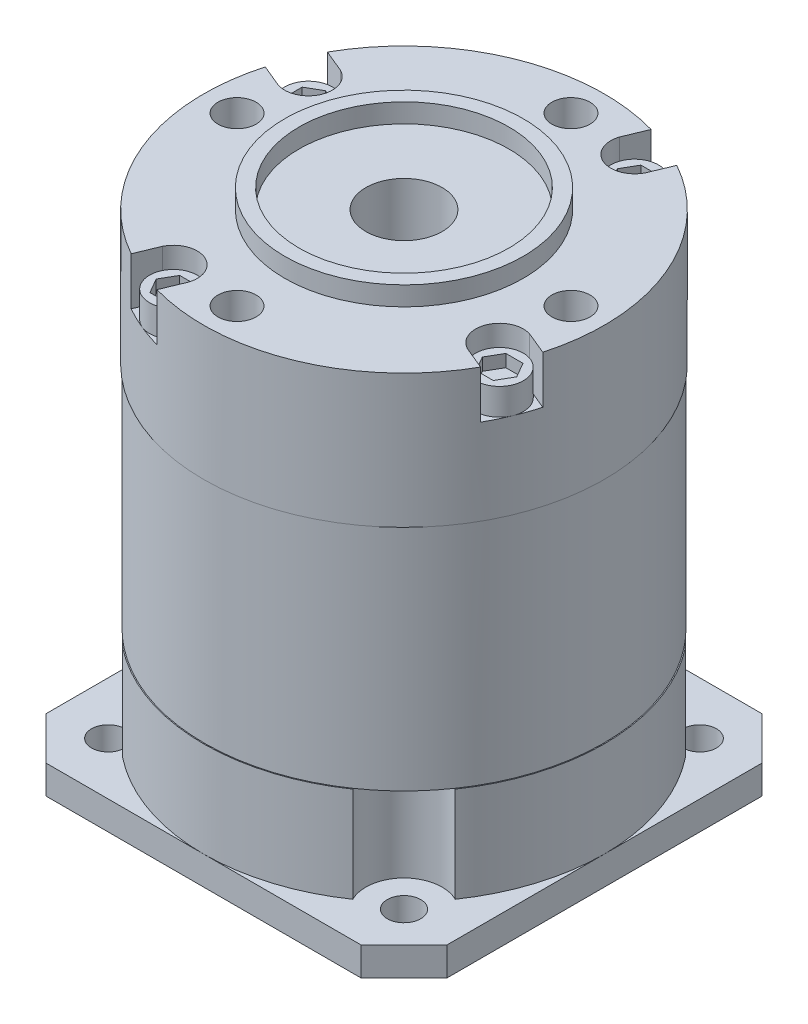
SolidWorks part; units mm, degrees
ref_plane "前视基准面" through (0, 0, 0) normal (0, 0, 1) x (1, 0, 0)
ref_plane "上视基准面" through (0, 0, 0) normal (0, 1, 0) x (1, 0, 0)
ref_plane "右视基准面" through (0, 0, 0) normal (1, 0, 0) x (0, 0, -1)
other "Configuration Table"
sketch "草图1" plane through (0, 0, 0) normal (0, 1, 0) x (1, 0, 0)
  line L1 (-21, 21) -> (21, 21)
  line L2 (-21, 21) -> (-21, -21)
  line L3 (-21, -21) -> (21, -21)
  line L4 (21, 21) -> (21, -21)
  line L5 (-21, 21) -> (21, -21) construction
  line L6 (-21, -21) -> (21, 21) construction
  point P0 (0, 0)
  dimension "D1" = 42
  dimension "D2" = 42
extrude "凸台-拉伸1" add sketch "草图1" along normal blind 3
sketch "草图2" plane through (0, 0, 0) normal (0, 1, 0) x (1, 0, 0)
  line L0 (-1000, 0) -> (49000, 0) construction
  line L1 (0, -1000) -> (0, 49000) construction
  line L2 (-21, 21) -> (-21, 16.5)
  line L3 (-21, 21) -> (-21, -21) construction
  line L4 (-21, 16.5) -> (-16.5, 21)
  line L5 (21, 21) -> (-21, 21) construction
  line L6 (-16.5, 21) -> (-21, 21)
  line L7 (16.5, 21) -> (21, 21)
  line L8 (21, 16.5) -> (16.5, 21)
  line L9 (21, 21) -> (21, 16.5)
  line L10 (21, -21) -> (21, -16.5)
  line L11 (21, -16.5) -> (16.5, -21)
  line L12 (16.5, -21) -> (21, -21)
  line L13 (-16.5, -21) -> (-21, -21)
  line L14 (-21, -16.5) -> (-16.5, -21)
  line L15 (-21, -21) -> (-21, -16.5)
  dimension "D1" = 4.5
  dimension "D2" = 4.5
extrude "切除-拉伸1" cut sketch "草图2" against normal up to surface (3 mm away) from surface at 3 up to face at (0, 0, 0) starting at face at (0, 3, 0)
sketch "草图3" plane through (0, 0, 0) normal (0, 1, 0) x (1, 0, 0)
  circle A0 centre (0, 0) radius 21
  dimension "D1" = 42
extrude "凸台-拉伸2" add sketch "草图3" along normal blind 51
sketch "草图5" plane through (0, 0, 0) normal (0, 1, 0) x (1, 0, 0)
  line L1 (-15.5, 15.5) -> (15.5, 15.5) construction
  line L2 (-15.5, 15.5) -> (-15.5, -15.5) construction
  line L3 (-15.5, -15.5) -> (15.5, -15.5) construction
  line L4 (15.5, 15.5) -> (15.5, -15.5) construction
  line L5 (-15.5, 15.5) -> (15.5, -15.5) construction
  line L6 (-15.5, -15.5) -> (15.5, 15.5) construction
  circle A0 centre (-15.5, 15.5) radius 1.75
  circle A1 centre (15.5, 15.5) radius 1.75
  circle A2 centre (-15.5, -15.5) radius 1.75
  circle A3 centre (15.5, -15.5) radius 1.75
  point P0 (0, 0)
  dimension "D3" = 3.5
  dimension "D4" = 3.5
  dimension "D5" = 3.5
  dimension "D6" = 3.5
  dimension "D1" = 31
  dimension "D2" = 31
extrude "切除-拉伸3" cut sketch "草图5" along normal up to surface (3 mm away) from surface at 0 up to face at (15.7123, 3, 15.7123) starting at face at (0, 0, 0)
sketch "草图7" plane through (0, 0, 0) normal (0, 1, 0) x (1, 0, 0)
  circle A0 centre (-15.5, 15.5) radius 2.75
  circle A1 centre (15.5, 15.5) radius 2.75
  circle A2 centre (-15.5, -15.5) radius 2.75
  circle A3 centre (15.5, -15.5) radius 4
  dimension "D1" = 5.5
  dimension "D2" = 5.5
  dimension "D3" = 5.5
  dimension "D4" = 8
extrude "切除-拉伸4" cut sketch "草图7" along normal blind 10 from surface at 3 starting at face at (15.2941, 3, -15.2941)
sketch "草图8" plane through (0, 0, 0) normal (0, 1, 0) x (1, 0, 0)
  circle A0 centre (0, 0) radius 20.9
  circle A1 centre (0, 0) radius 21
  dimension "D1" = 41.8
  dimension "D2" = 42
extrude "切除-拉伸5" cut sketch "草图8" along normal blind 24 from surface at 13 starting at face at (13.7604, 13, 13.7604)
sketch "草图9" plane through (0, 0, 0) normal (0, 1, 0) x (1, 0, 0)
  circle A0 centre (0, 0) radius 12.5
  dimension "D1" = 25
extrude "凸台-拉伸3" add sketch "草图9" along normal blind 2 from surface at 51 starting at face at (0, 51, 21)
sketch "草图11" plane through (0, 0, 0) normal (0, 1, 0) x (1, 0, 0)
  line L0 (-1000, 0) -> (49000, 0) construction
  line L1 (0, -1000) -> (0, 49000) construction
  circle A0 centre (0, 0) radius 17.5 construction
  circle A1 centre (-17.5, 0) radius 2
  circle A2 centre (0, -17.5) radius 2
  circle A3 centre (17.5, 0) radius 2
  circle A4 centre (0, 17.5) radius 2
  point P7 (0, 17.5)
  point P8 (-17.5, 0)
  point P9 (17.5, 0)
  point P10 (0, -17.5)
  point P11 (22.5067, -42.5527)
  dimension "D1" = 35
  dimension "D2" = 4
  dimension "D3" = 4
  dimension "D4" = 4
  dimension "D5" = 4
sketch "草图16" plane through (0, 0, 0) normal (0, 1, 0) x (1, 0, 0)
  circle A0 centre (0, 0) radius 11
  dimension "D1" = 22
extrude "切除-拉伸6" cut sketch "草图16" against normal up to surface (2 mm away) from surface at 53 up to face at (0, 51, 12.5) starting at face at (0, 53, 12.5)
sketch "草图17" plane through (0, 0, 0) normal (0, 1, 0) x (1, 0, 0)
  line L0 (-1000, 0) -> (49000, 0) construction
  line L1 (0, -1000) -> (0, 49000) construction
  line L2 (0, 0) -> (19134.1716, 46193.9766) construction
  line L3 (0, 0) -> (46193.9766, -19134.1716) construction
  line L4 (-18.3096, 10.2839) -> (-15.9812, 9.3194)
  line L5 (-20.2187, 5.675) -> (-17.8902, 4.7106)
  line L6 (18.3096, -10.2839) -> (15.9812, -9.3194)
  line L7 (20.2187, -5.675) -> (17.8902, -4.7106)
  line L8 (-4.7106, -17.8902) -> (-5.675, -20.2187)
  line L9 (-9.3194, -15.9812) -> (-10.2839, -18.3096)
  line L10 (4.7106, 17.8902) -> (5.675, 20.2187)
  line L11 (9.3194, 15.9812) -> (10.2839, 18.3096)
  arc A1 (-18.2024, 4.8399) -> (-16.2933, 9.4487) centre (-17.0918, 7.0796) ccw
  arc A2 (-4.8399, -18.2024) -> (-9.4487, -16.2933) centre (-7.0796, -17.0918) ccw
  arc A3 (18.2024, -4.8399) -> (16.2933, -9.4487) centre (17.0918, -7.0796) ccw
  arc A4 (4.8399, 18.2024) -> (9.4487, 16.2933) centre (7.0796, 17.0918) ccw
  circle A5 centre (0, 0) radius 21 construction
  arc A6 (-10.2839, -18.3096) -> (-5.675, -20.2187) centre (0, 0) ccw
  arc A7 (17.2879, -11.9218) -> (21, 0) centre (0, 0) ccw construction
  circle A8 centre (0, 0) radius 18.5 construction
  arc A9 (-18.3096, 10.2839) -> (-20.2187, 5.675) centre (0, 0) ccw
  arc A10 (10.2839, 18.3096) -> (5.675, 20.2187) centre (0, 0) ccw
  arc A11 (18.3096, -10.2839) -> (20.2187, -5.675) centre (0, 0) ccw
  point P12 (7.0796, 17.0918)
  point P13 (17.0918, -7.0796)
  point P14 (-7.0796, -17.0918)
  point P15 (-17.0918, 7.0796)
  dimension "D3" = 37
  dimension "D1" = 22.5
  dimension "D2" = 22.5
extrude "切除-拉伸7" cut sketch "草图17" against normal blind 5 from surface at 51 contours L6 A11 L7 A3 | L9 A6 L8 A2 | L4 A9 L5 A1 | L11 A10 L10 A4 starting at face at (0, 51, 12.5)
sketch "草图18" plane through (0, 0, 0) normal (0, 1, 0) x (1, 0, 0)
  line L1 (-15.5329, 7.9796) -> (-17.0918, 8.8796)
  line L2 (-17.0918, 8.8796) -> (-18.6506, 7.9796)
  line L3 (-18.6506, 7.9796) -> (-18.6506, 6.1796)
  line L4 (-18.6506, 6.1796) -> (-17.0918, 5.2796)
  line L5 (-17.0918, 5.2796) -> (-15.5329, 6.1796)
  line L6 (-15.5329, 6.1796) -> (-15.5329, 7.9796)
  line L7 (7.9796, 15.5329) -> (8.8796, 17.0918)
  line L8 (8.8796, 17.0918) -> (7.9796, 18.6506)
  line L9 (7.9796, 18.6506) -> (6.1796, 18.6506)
  line L10 (6.1796, 18.6506) -> (5.2796, 17.0918)
  line L11 (5.2796, 17.0918) -> (6.1796, 15.5329)
  line L12 (6.1796, 15.5329) -> (7.9796, 15.5329)
  line L13 (18.8918, -7.0796) -> (17.9918, -5.5208)
  line L14 (17.9918, -5.5208) -> (16.1918, -5.5208)
  line L15 (16.1918, -5.5208) -> (15.2918, -7.0796)
  line L16 (15.2918, -7.0796) -> (16.1918, -8.6385)
  line L17 (16.1918, -8.6385) -> (17.9918, -8.6385)
  line L18 (17.9918, -8.6385) -> (18.8918, -7.0796)
  line L19 (-6.1796, -18.6506) -> (-5.2796, -17.0918)
  line L20 (-5.2796, -17.0918) -> (-6.1796, -15.5329)
  line L21 (-6.1796, -15.5329) -> (-7.9796, -15.5329)
  line L22 (-7.9796, -15.5329) -> (-8.8796, -17.0918)
  line L23 (-8.8796, -17.0918) -> (-7.9796, -18.6506)
  line L24 (-7.9796, -18.6506) -> (-6.1796, -18.6506)
  circle A0 centre (-17.0918, 7.0796) radius 2.5
  circle A1 centre (-7.0796, -17.0918) radius 2.5
  circle A2 centre (17.0918, -7.0796) radius 2.5
  circle A3 centre (7.0796, 17.0918) radius 2.5
  circle A4 centre (-17.0918, 7.0796) radius 1.5588 construction
  circle A5 centre (7.0796, 17.0918) radius 1.5588 construction
  circle A6 centre (17.0918, -7.0796) radius 1.5588 construction
  circle A7 centre (-7.0796, -17.0918) radius 1.5588 construction
  dimension "D1" = 1.8
  dimension "D2" = 1.8
  dimension "D3" = 1.8
  dimension "D4" = 1.8
extrude "凸台-拉伸5" add sketch "草图18" along normal blind 2.8 from surface at 46 starting at face at (-7.2884, 46, 17.5958)
sketch "草图19" plane through (0, 0, 0) normal (0, 1, 0) x (1, 0, 0)
  circle A0 centre (0, 0) radius 4
  dimension "D1" = 8
extrude "切除-拉伸8" cut sketch "草图19" along normal up to surface (51 mm away) from surface at 0 up to face at (0, 51, 11) starting at face at (15.5, 0, -13.75)
sketch "草图20" plane through (0, 0, 0) normal (0, 1, 0) x (1, 0, 0)
  line L0 (7.9796, 18.6506) -> (6.1796, 18.6506) construction
  line L1 (6.1796, 18.6506) -> (5.2796, 17.0918) construction
  line L2 (5.2796, 17.0918) -> (6.1796, 15.5329) construction
  line L3 (6.1796, 15.5329) -> (7.9796, 15.5329) construction
  line L4 (7.9796, 15.5329) -> (8.8796, 17.0918) construction
  line L5 (8.8796, 17.0918) -> (7.9796, 18.6506) construction
  line L6 (16.1918, -5.5208) -> (15.2918, -7.0796) construction
  line L7 (15.2918, -7.0796) -> (16.1918, -8.6385) construction
  line L8 (16.1918, -8.6385) -> (17.9918, -8.6385) construction
  line L9 (17.9918, -8.6385) -> (18.8918, -7.0796) construction
  line L10 (18.8918, -7.0796) -> (17.9918, -5.5208) construction
  line L11 (17.9918, -5.5208) -> (16.1918, -5.5208) construction
  line L12 (-6.1796, -15.5329) -> (-7.9796, -15.5329) construction
  line L13 (-7.9796, -15.5329) -> (-8.8796, -17.0918) construction
  line L14 (-8.8796, -17.0918) -> (-7.9796, -18.6506) construction
  line L15 (-7.9796, -18.6506) -> (-6.1796, -18.6506) construction
  line L16 (-6.1796, -18.6506) -> (-5.2796, -17.0918) construction
  line L17 (-5.2796, -17.0918) -> (-6.1796, -15.5329) construction
  line L18 (-18.6506, 7.9796) -> (-18.6506, 6.1796) construction
  line L19 (-18.6506, 6.1796) -> (-17.0918, 5.2796) construction
  line L20 (-17.0918, 5.2796) -> (-15.5329, 6.1796) construction
  line L21 (-15.5329, 6.1796) -> (-15.5329, 7.9796) construction
  line L22 (-15.5329, 7.9796) -> (-17.0918, 8.8796) construction
  line L23 (-17.0918, 8.8796) -> (-18.6506, 7.9796) construction
  line L24 (7.9796, 18.6506) -> (6.1796, 18.6506)
  line L25 (6.1796, 18.6506) -> (5.2796, 17.0918)
  line L26 (5.2796, 17.0918) -> (6.1796, 15.5329)
  line L27 (6.1796, 15.5329) -> (7.9796, 15.5329)
  line L28 (7.9796, 15.5329) -> (8.8796, 17.0918)
  line L29 (8.8796, 17.0918) -> (7.9796, 18.6506)
  line L30 (16.1918, -5.5208) -> (15.2918, -7.0796)
  line L31 (15.2918, -7.0796) -> (16.1918, -8.6385)
  line L32 (16.1918, -8.6385) -> (17.9918, -8.6385)
  line L33 (17.9918, -8.6385) -> (18.8918, -7.0796)
  line L34 (18.8918, -7.0796) -> (17.9918, -5.5208)
  line L35 (17.9918, -5.5208) -> (16.1918, -5.5208)
  line L36 (-6.1796, -15.5329) -> (-7.9796, -15.5329)
  line L37 (-7.9796, -15.5329) -> (-8.8796, -17.0918)
  line L38 (-8.8796, -17.0918) -> (-7.9796, -18.6506)
  line L39 (-7.9796, -18.6506) -> (-6.1796, -18.6506)
  line L40 (-6.1796, -18.6506) -> (-5.2796, -17.0918)
  line L41 (-5.2796, -17.0918) -> (-6.1796, -15.5329)
  line L42 (-18.6506, 7.9796) -> (-18.6506, 6.1796)
  line L43 (-18.6506, 6.1796) -> (-17.0918, 5.2796)
  line L44 (-17.0918, 5.2796) -> (-15.5329, 6.1796)
  line L45 (-15.5329, 6.1796) -> (-15.5329, 7.9796)
  line L46 (-15.5329, 7.9796) -> (-17.0918, 8.8796)
  line L47 (-17.0918, 8.8796) -> (-18.6506, 7.9796)
extrude "凸台-拉伸6" add sketch "草图20" along normal blind 1.5 from surface at 46 starting at face at (-17.0918, 46, -7.0796)
sketch "草图21" plane through (0, 0, 0) normal (0, 1, 0) x (1, 0, 0)
  circle A0 centre (0, 0) radius 12.5
  dimension "D1" = 25
extrude "切除-拉伸9" cut sketch "草图21" along normal blind 3
extrude "切除-拉伸11" cut sketch "草图11" against normal blind 8 from surface at 51 starting at face at (0, 51, 12.5)
